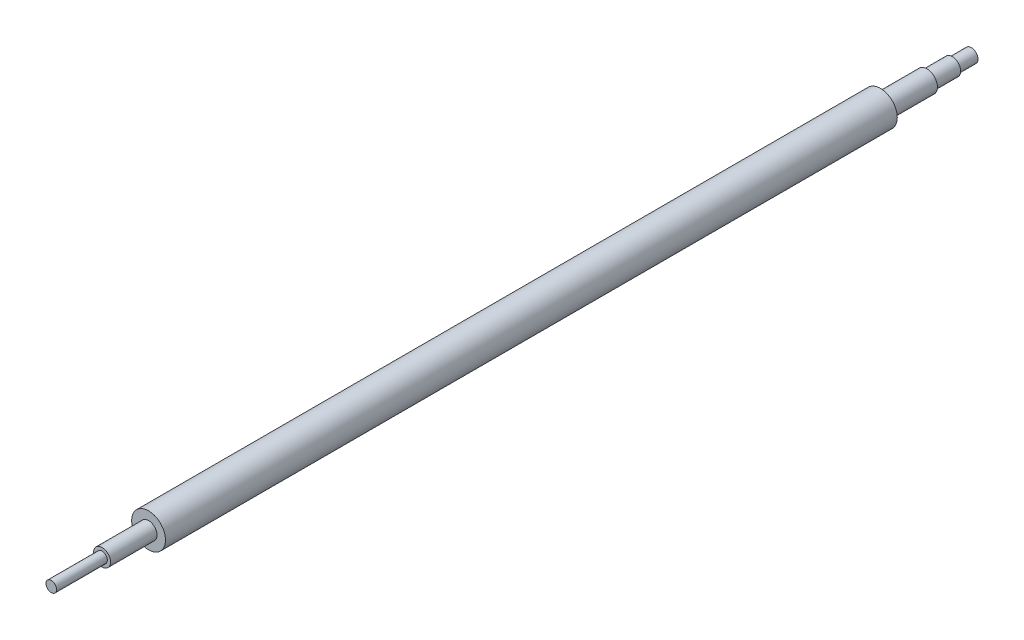
SolidWorks part; units mm, degrees
ref_plane "前视基准面" through (0, 0, 0) normal (0, 0, 1) x (1, 0, 0)
ref_plane "上视基准面" through (0, 0, 0) normal (0, 1, 0) x (1, 0, 0)
ref_plane "右视基准面" through (0, 0, 0) normal (1, 0, 0) x (0, 0, -1)
sketch "草图1" plane through (0, 0, 0) normal (0, 0, 1) x (1, 0, 0)
  circle A0 centre (0, 0) radius 8
  dimension "D1" = 16
extrude "凸台-拉伸1" add sketch "草图1" along normal blind 346
sketch "草图2" plane through (0, 0, 346) normal (0, 0, 1) x (1, 0, 0)
  circle A0 centre (0, 0) radius 4
  dimension "D1" = 8
extrude "凸台-拉伸2" add sketch "草图2" along normal blind 22 separate body
sketch "草图4" plane through (0, 0, 0) normal (0, 0, -1) x (-1, 0, 0)
  circle A0 centre (0, 0) radius 5
  dimension "D1" = 10
extrude "凸台-拉伸3" add sketch "草图4" along normal blind 22 separate body
sketch "草图5" plane through (0, 0, 368) normal (0, 0, 1) x (1, 0, 0)
  circle A0 centre (0, 0) radius 2.5
  dimension "D1" = 5
extrude "凸台-拉伸4" add sketch "草图5" along normal blind 24
sketch "草图9" plane through (0, 0, -22) normal (0, 0, -1) x (-1, 0, 0)
  circle A0 centre (0, 0) radius 4
extrude "凸台-拉伸5" add sketch "草图9" along normal blind 12
sketch "草图10" plane through (0, 0, -34) normal (0, 0, -1) x (-1, 0, 0)
  circle A2 centre (0, 0) radius 3.175
extrude "凸台-拉伸6" add sketch "草图10" along normal blind 9
